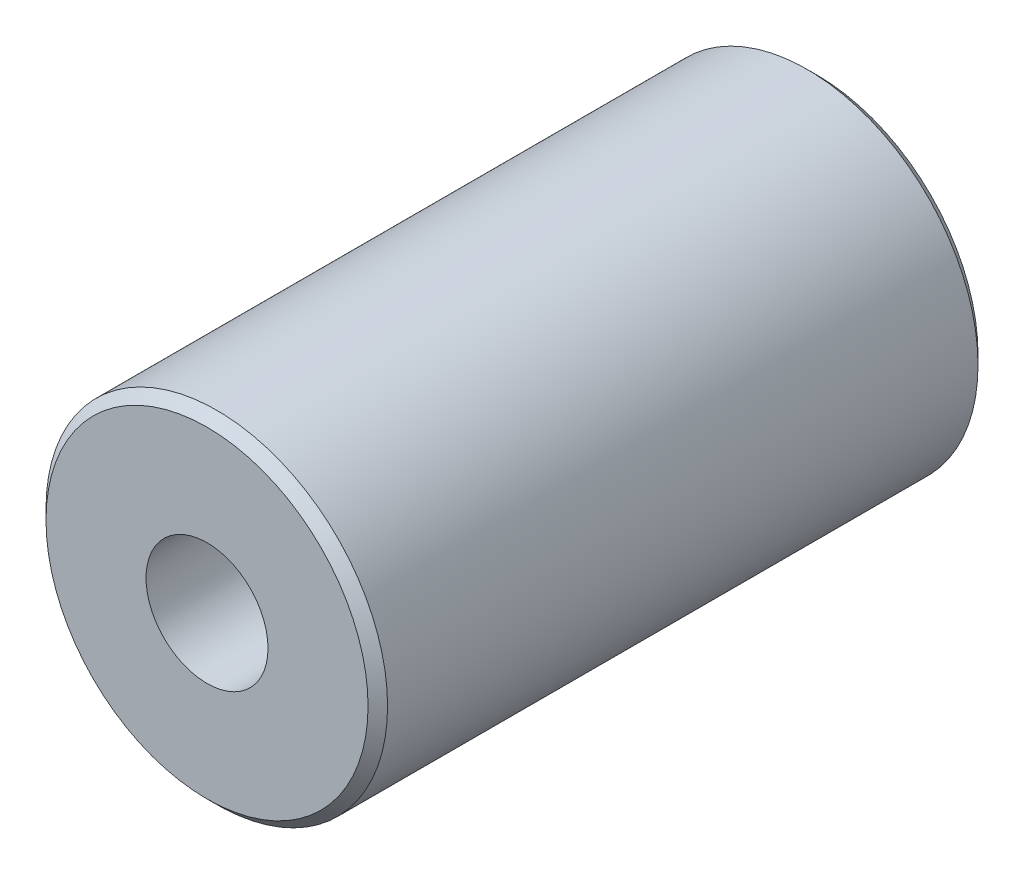
SolidWorks part; units mm, degrees
ref_plane "Front Plane" through (0, 0, 0) normal (0, 0, 1) x (1, 0, 0)
ref_plane "Top Plane" through (0, 0, 0) normal (0, 1, 0) x (1, 0, 0)
ref_plane "Right Plane" through (0, 0, 0) normal (1, 0, 0) x (0, 0, -1)
sketch "Sketch1" plane through (0, 0, 0) normal (0, 0, 1) x (1, 0, 0)
  circle A0 centre (0, 0) radius 7
  dimension "D1" = 14
extrude "Boss-Extrude1" add sketch "Sketch1" along normal mid plane 25
sketch "Sketch2" plane through (0, 0, 12.5) normal (0, 0, 1) x (1, 0, 0)
  circle A0 centre (0, 0) radius 2.5
  dimension "D1" = 5
extrude "Cut-Extrude1" cut sketch "Sketch2" against normal through all
sketch "Sketch3" plane through (0, 0, 0) normal (0, 0, 1) x (1, 0, 0)
  circle A0 centre (0, 0) radius 4
  dimension "D1" = 8
extrude "Cut-Extrude2" cut sketch "Sketch3" against normal through all
chamfer "Chamfer1" distance 0.4 angle 45 2 edges at (7, 0, 12.5) (7, 0, -12.5)
